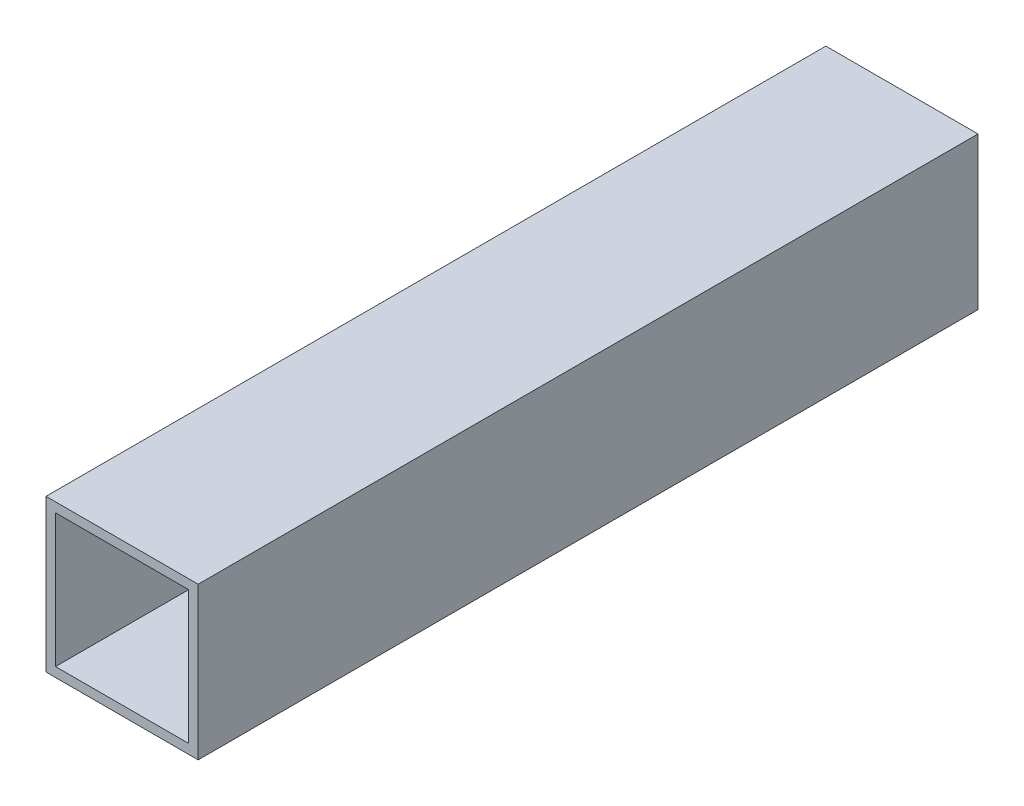
SolidWorks part; units mm, degrees
ref_plane "Front Plane" through (0, 0, 0) normal (0, 0, 1) x (1, 0, 0)
ref_plane "Top Plane" through (0, 0, 0) normal (0, 1, 0) x (1, 0, 0)
ref_plane "Right Plane" through (0, 0, 0) normal (1, 0, 0) x (0, 0, -1)
sketch "Sketch1" plane through (0, 0, 0) normal (0, 0, 1) x (1, 0, 0)
  line L0 (-22.225, 22.225) -> (22.225, 22.225)
  line L1 (-25.4, -25.4) -> (25.4, -25.4)
  line L2 (-25.4, -25.4) -> (-25.4, 25.4)
  line L3 (-25.4, 25.4) -> (25.4, 25.4)
  line L4 (25.4, -25.4) -> (25.4, 25.4)
  line L5 (-25.4, -25.4) -> (25.4, 25.4) construction
  line L6 (-25.4, 25.4) -> (25.4, -25.4) construction
  line L7 (22.225, -22.225) -> (22.225, 22.225)
  line L8 (-22.225, -22.225) -> (22.225, -22.225)
  line L9 (-22.225, -22.225) -> (-22.225, 22.225)
  point P0 (0, 0)
  dimension "D1" = 3.175
  dimension "tube_width" = 50.8
  dimension "D2" = 50.8
extrude "Boss-Extrude1" add sketch "Sketch1" along normal blind 260.35
